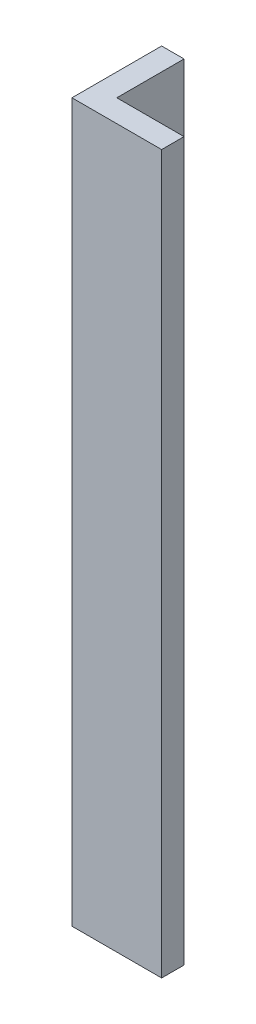
SolidWorks part; units mm, degrees
ref_plane "Front Plane" through (0, 0, 0) normal (0, 0, 1) x (1, 0, 0)
ref_plane "Top Plane" through (0, 0, 0) normal (0, 1, 0) x (1, 0, 0)
ref_plane "Right Plane" through (0, 0, 0) normal (1, 0, 0) x (0, 0, -1)
sketch "Sketch1" plane through (0, 0, 0) normal (0, 1, 0) x (1, 0, 0)
  line L1 (0, 0) -> (6.35, 0)
  line L2 (0, 0) -> (0, 6.35)
  line L3 (0, 6.35) -> (1.5875, 6.35)
  line L4 (6.35, 0) -> (6.35, 1.5875)
  line L7 (6.35, 1.5875) -> (1.5875, 1.5875)
  line L8 (1.5875, 6.35) -> (1.5875, 1.5875)
  dimension "D1" = 6.35
  dimension "D2" = 6.35
  dimension "D3" = 1.5875
  dimension "D4" = 1.5875
extrude "Boss-Extrude1" add sketch "Sketch1" along normal blind 50.8
